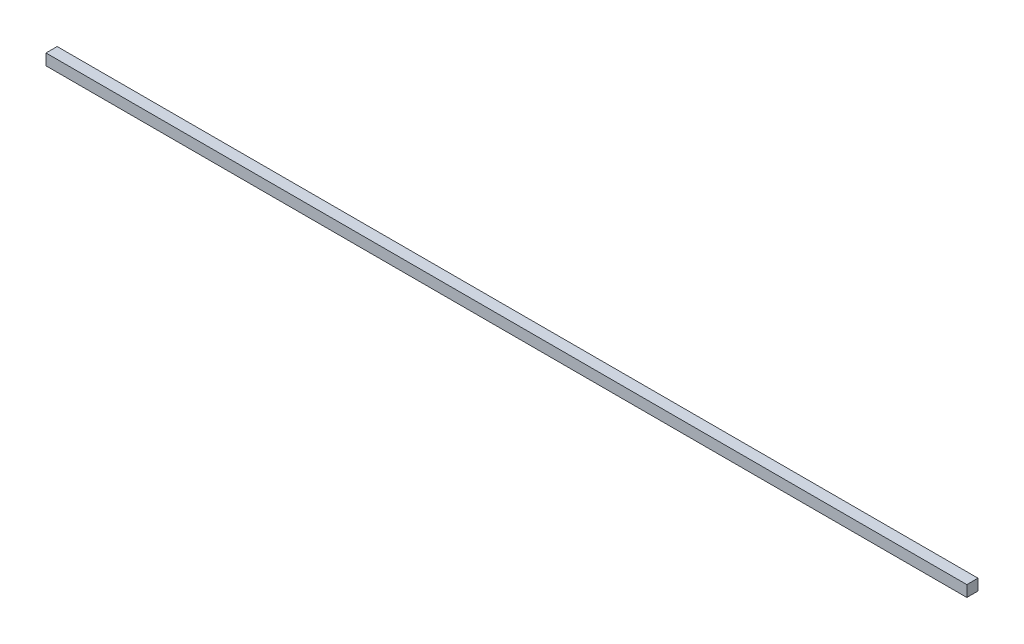
SolidWorks part; units mm, degrees
ref_plane "Front Plane" through (0, 0, 0) normal (0, 0, 1) x (1, 0, 0)
ref_plane "Top Plane" through (0, 0, 0) normal (0, 1, 0) x (1, 0, 0)
ref_plane "Right Plane" through (0, 0, 0) normal (1, 0, 0) x (0, 0, -1)
other "Configuration Table"
sketch "Sketch1" plane through (0, 0, 0) normal (0, 0, 1) x (1, 0, 0)
  line L1 (20, 1152) -> (680, 1152)
  line L2 (20, 1152) -> (20, 1160)
  line L3 (20, 1160) -> (680, 1160)
  line L4 (680, 1152) -> (680, 1160)
extrude "TOPPING_klape_kat2_pivot_mil_1" add sketch "Sketch1" along normal blind 8 from offset 22 separate body
